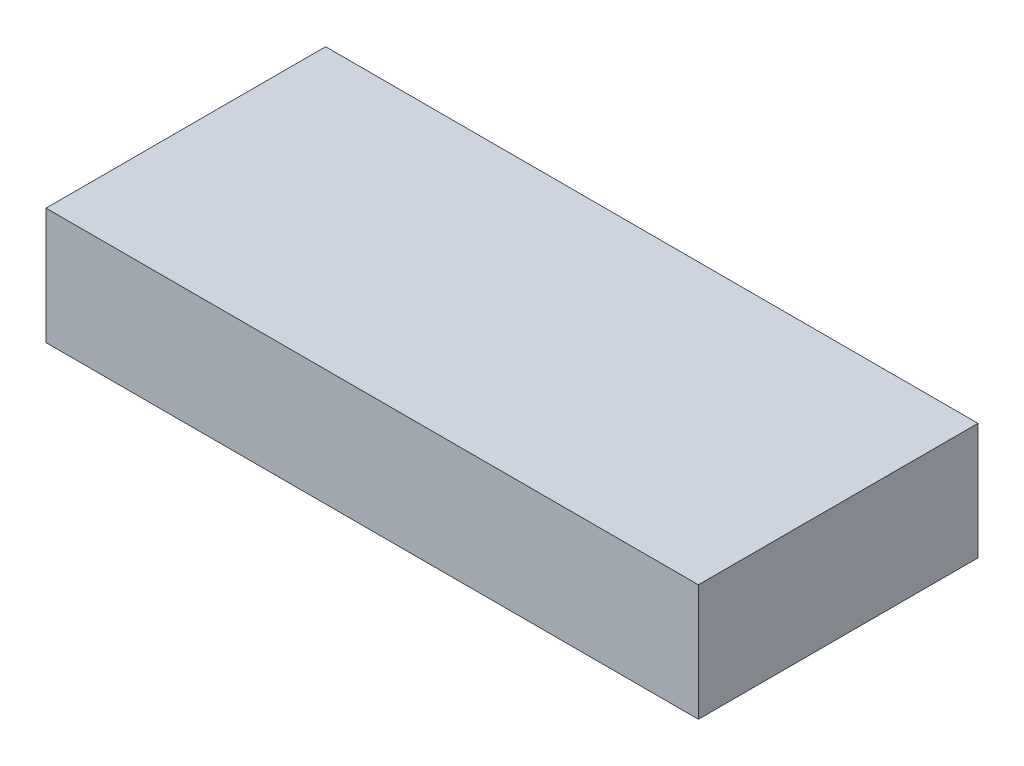
SolidWorks part; units mm, degrees
ref_plane "Front Plane" through (0, 0, 0) normal (0, 0, 1) x (1, 0, 0)
ref_plane "Top Plane" through (0, 0, 0) normal (0, 1, 0) x (1, 0, 0)
ref_plane "Right Plane" through (0, 0, 0) normal (1, 0, 0) x (0, 0, -1)
sketch "Sketch1" plane through (0, 0, 0) normal (0, 1, 0) x (1, 0, 0)
  line L1 (140, -60) -> (-140, -60)
  line L2 (140, -60) -> (140, 60)
  line L3 (140, 60) -> (-140, 60)
  line L4 (-140, -60) -> (-140, 60)
  line L5 (140, -60) -> (-140, 60) construction
  line L6 (140, 60) -> (-140, -60) construction
  point P0 (0, 0)
  dimension "D1" = 280
  dimension "D2" = 120
extrude "Boss-Extrude1" add sketch "Sketch1" along normal mid plane 50
